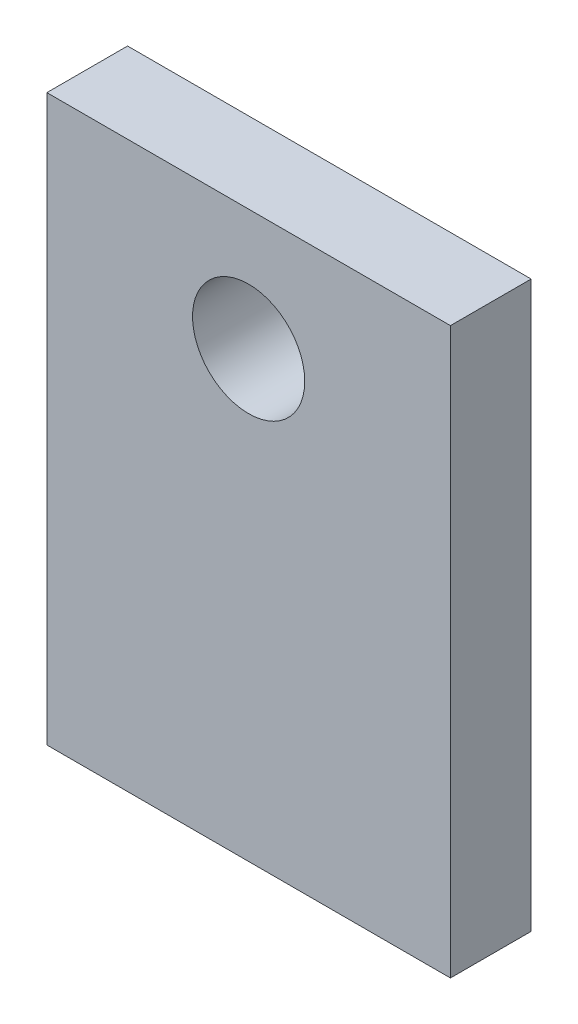
SolidWorks part; units mm, degrees
ref_plane "Front" through (0, 0, 0) normal (0, 0, 1) x (1, 0, 0)
ref_plane "Top" through (0, 0, 0) normal (0, 1, 0) x (1, 0, 0)
ref_plane "Right" through (0, 0, 0) normal (1, 0, 0) x (0, 0, -1)
sketch "Sketch1" plane through (0, 0, 0) normal (0, 0, 1) x (1, 0, 0)
  line L1 (0, 0) -> (127, 0)
  line L2 (0, 0) -> (0, 177.8)
  line L3 (0, 177.8) -> (127, 177.8)
  line L4 (127, 0) -> (127, 177.8)
  circle A0 centre (63.5, 139.7) radius 17.653
  dimension "D3" = 38.1
  dimension "D5" = 35.306
  dimension "D1" = 127
  dimension "D2" = 177.8
  dimension "D4" = 63.5
extrude "Base-Extrude" add sketch "Sketch1" along normal blind 25.4
